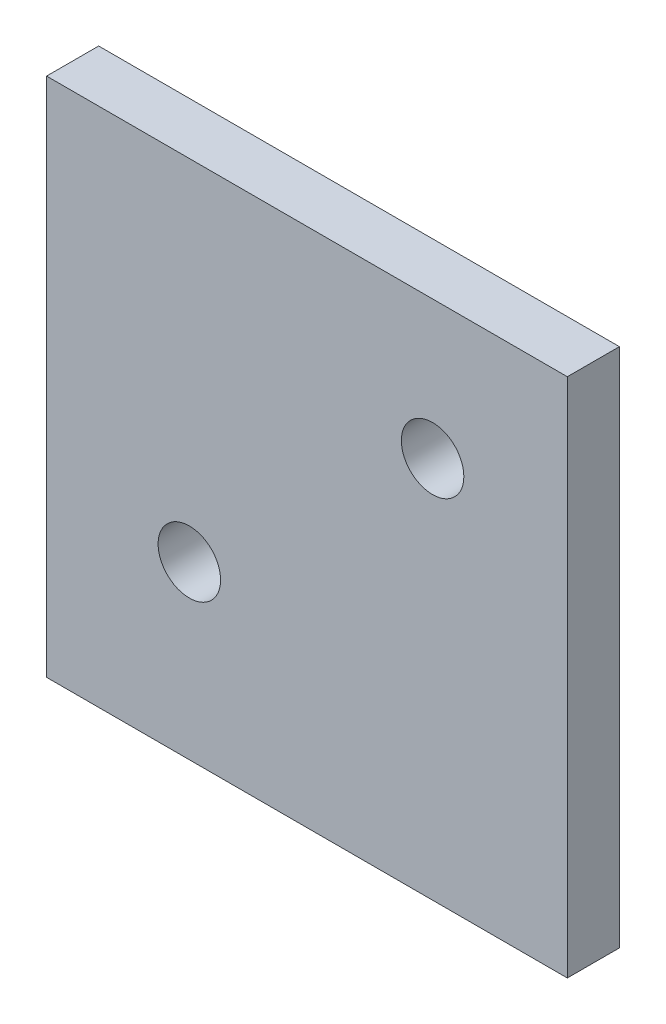
SolidWorks part; units mm, degrees
ref_plane "Спереди" through (0, 0, 0) normal (0, 0, 1) x (1, 0, 0)
ref_plane "Сверху" through (0, 0, 0) normal (0, 1, 0) x (1, 0, 0)
ref_plane "Справа" through (0, 0, 0) normal (1, 0, 0) x (0, 0, -1)
sketch "Эскиз1" plane through (0, 0, 0) normal (0, 0, 1) x (1, 0, 0)
  line L0 (-35.0379, 37.8788) -> (64.9621, 37.8788)
  line L1 (64.9621, 37.8788) -> (64.9621, -62.1212)
  line L2 (64.9621, -62.1212) -> (-35.0379, -62.1212)
  line L3 (-35.0379, -62.1212) -> (-35.0379, 37.8788)
extrude "Бобышка-Вытянуть1" add sketch "Эскиз1" along normal blind 10
sketch "Эскиз5" plane through (0, 0, 10) normal (0, 0, 1) x (1, 0, 0)
  point P0 (39.0875, 11.3313)
  point P2 (-7.6253, -29.23)
hole_wizard "Диаметр отверстия Ø12.0 (12)1" positions "Эскиз5" profile "Эскиз3" hole size "Ø12.0" standard "ISO" end condition through all
sketch "Эскиз3" plane through (39.0875, 11.3313, 10) normal (1, 0, 0) x (0, -1, 0)
  line L0 (0, 0) -> (0, 10)
  line L1 (0, 10) -> (6, 10)
  line L2 (6, 10) -> (6, 0)
  line L5 (6, 0) -> (0, 0)
  line L11 (0, -6.35) -> (0, 107.95) construction
  dimension "Äèàìåòð ñêâîçíîãî îòâåðñòèÿ" = 12
  dimension "Ãëóáèíà ñêâîçíîãî îòâåðñòèÿ" = 10
